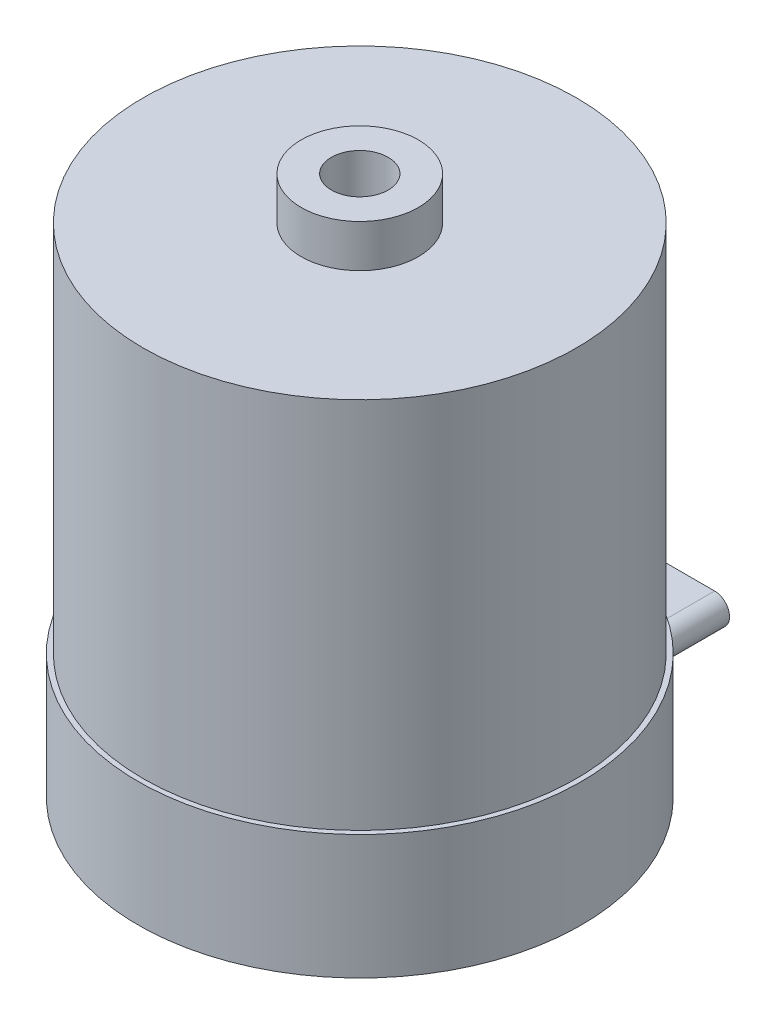
SolidWorks part; units mm, degrees
ref_plane "Top Plane" through (0, 0, 0) normal (0, 0, 1) x (1, 0, 0)
ref_plane "Front Plane" through (0, 0, 0) normal (0, 1, 0) x (1, 0, 0)
ref_plane "Right Plane" through (0, 0, 0) normal (1, 0, 0) x (0, 0, -1)
sketch "Sketch2" plane through (0, 0, 0) normal (0, 0, 1) x (1, 0, 0)
  line L0 (4, 0) -> (4, 76)
  line L1 (4, 76) -> (8.25, 76)
  line L2 (8.25, 76) -> (8.25, 70)
  line L3 (8.25, 70) -> (30.5, 70)
  line L4 (30.5, 70) -> (30.5, 17.5)
  line L5 (30.5, 17.5) -> (31.2, 17.5)
  line L6 (31.2, 17.5) -> (31.2, 0)
  line L7 (31.2, 0) -> (4, 0)
  line L8 (0, 0) -> (0, 76) construction
  dimension "D1" = 4
  dimension "D2" = 27.2
  dimension "D3" = 17.5
  dimension "D4" = 26.5
  dimension "D5" = 6
  dimension "D6" = 52.5
  dimension "D7" = 4.25
revolve "Revolve1" add sketch "Sketch2" angle 360 about L8
sketch "Sketch3" plane through (0, 0, 0) normal (0, -1, 0) x (1, 0, 0)
  line L0 (15.5563, -15.5563) -> (-15.5563, -15.5563) construction
  line L1 (-15.5563, -15.5563) -> (-15.5563, 15.5563) construction
  line L2 (-15.5563, 15.5563) -> (15.5563, 15.5563) construction
  line L3 (15.5563, 15.5563) -> (15.5563, -15.5563) construction
  line L4 (15.5563, 15.5563) -> (-15.5563, -15.5563) construction
  circle A8 centre (15.5563, -15.5563) radius 1.65
  circle A9 centre (-15.5563, -15.5563) radius 1.65
  circle A10 centre (-15.5563, 15.5563) radius 1.65
  circle A11 centre (15.5563, 15.5563) radius 1.65
  point P8 (0, 0)
  dimension "D1" = 3.3
  dimension "D2" = 44
extrude "Cut-Extrude1" cut sketch "Sketch3" against normal blind 5
ref_plane "Plane1" through (0, 0, -31.2) normal (0, 0, -1) x (-1, 0, 0)
sketch "Sketch4" plane through (0, 0, -31.2) normal (0, 0, -1) x (-1, 0, 0)
  line L0 (-5.75, 3.8) -> (5.75, 3.8) construction
  line L1 (-5.75, 5.9) -> (5.75, 5.9)
  line L2 (-5.75, 1.7) -> (5.75, 1.7)
  line L3 (-31.2, 0) -> (31.2, 0) construction
  arc A0 (-5.75, 5.9) -> (-5.75, 1.7) centre (-5.75, 3.8) ccw
  arc A1 (5.75, 1.7) -> (5.75, 5.9) centre (5.75, 3.8) ccw
  point P2 (0, 3.8)
  dimension "D2" = 2.1
  dimension "D1" = 3.8
  dimension "D3" = 11.5
extrude "Boss-Extrude1" add sketch "Sketch4" along normal blind 15 from offset 2 offset against normal yes
ref_plane "Plane2" through (0, 0, 0) normal (-1, 0, 0) x (0, -1, 0)
